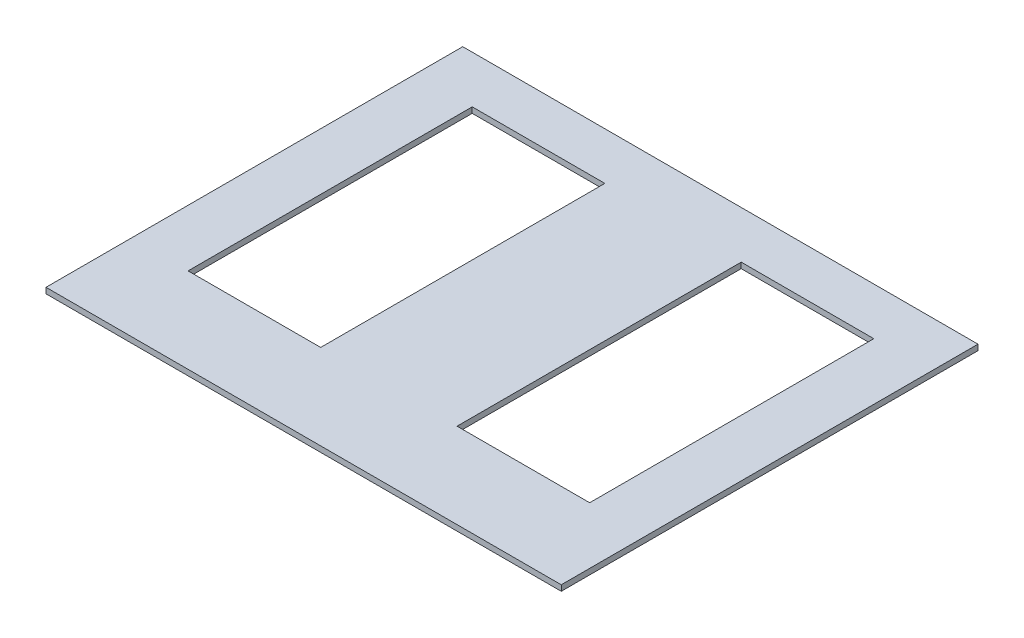
SolidWorks part; units mm, degrees
ref_plane "Front Plane" through (0, 0, 0) normal (0, 0, 1) x (1, 0, 0)
ref_plane "Top Plane" through (0, 0, 0) normal (0, 1, 0) x (1, 0, 0)
ref_plane "Right Plane" through (0, 0, 0) normal (1, 0, 0) x (0, 0, -1)
sketch "Sketch1" plane through (0, 0, 0) normal (0, 1, 0) x (1, 0, 0)
  line L1 (136, 110) -> (-136, 110)
  line L2 (136, 110) -> (136, -110)
  line L3 (136, -110) -> (-136, -110)
  line L4 (-136, 110) -> (-136, -110)
  line L5 (136, 110) -> (-136, -110) construction
  line L6 (136, -110) -> (-136, 110) construction
  point P0 (0, 0)
  dimension "D1" = 272
  dimension "D2" = 220
extrude "Boss-Extrude1" add sketch "Sketch1" along normal blind 3
sketch "Sketch2" plane through (0, 3, 0) normal (0, 1, 0) x (1, 0, 0)
  line L0 (-136, 110) -> (136, -110) construction
  line L1 (-136, -110) -> (136, 110) construction
  line L2 (136, 110) -> (136, 0) construction
  line L3 (136, -110) -> (136, 110) construction
  line L4 (136, 0) -> (-136, 0) construction
  line L5 (-136, 110) -> (-136, -110) construction
  line L6 (-136, 0) -> (0, 110) construction
  line L7 (136, 110) -> (-136, 110) construction
  line L8 (0, 110) -> (0, -110) construction
  line L9 (-136, -110) -> (136, -110) construction
  line L10 (106, -65) -> (36, 85) construction
  line L11 (-106, 85) -> (-36, 85)
  line L12 (-106, 85) -> (-106, -65)
  line L13 (-106, -65) -> (-36, -65)
  line L14 (-36, 85) -> (-36, -65)
  line L15 (-106, 85) -> (-36, -65) construction
  line L16 (-106, -65) -> (-36, 85) construction
  line L21 (106, 85) -> (36, -65) construction
  line L22 (36, 85) -> (36, -65)
  line L23 (106, -65) -> (36, -65)
  line L24 (106, 85) -> (106, -65)
  line L25 (106, 85) -> (36, 85)
  point P20 (-71, 10)
  point P29 (71, 10)
  dimension "D1" = 70
  dimension "D2" = 150
  dimension "D3" = 65
  dimension "D4" = 120
extrude "Cut-Extrude1" cut sketch "Sketch2" against normal through all
